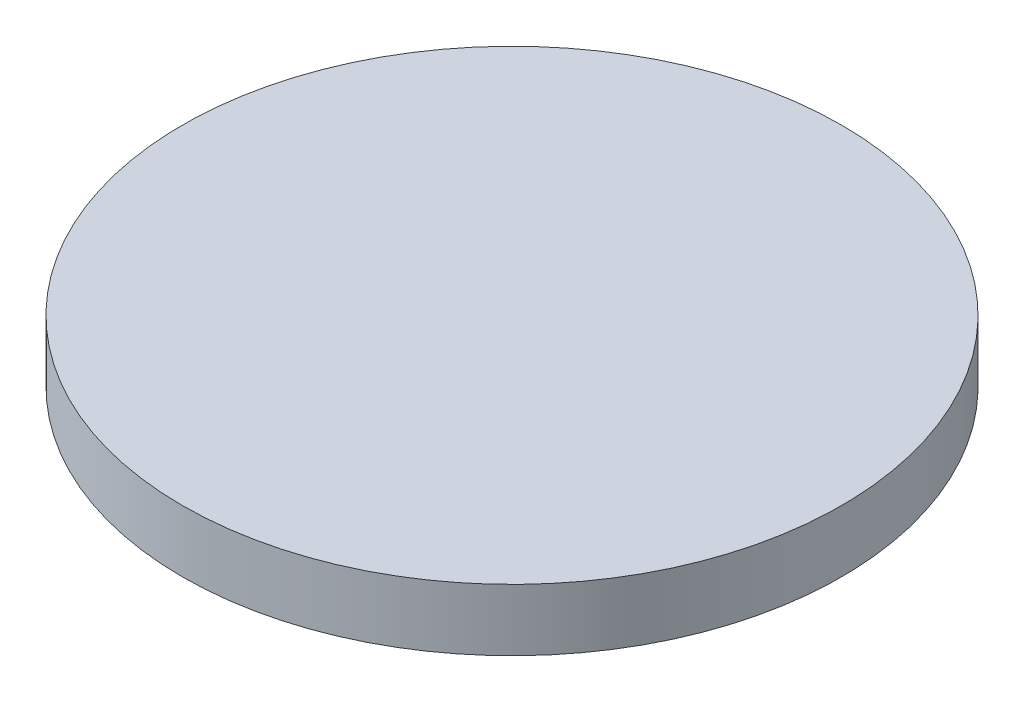
SolidWorks part; units mm, degrees
material "ABS PC"
ref_plane "Front Plane" through (0, 0, 0) normal (0, 0, 1) x (1, 0, 0)
ref_plane "Top Plane" through (0, 0, 0) normal (0, 1, 0) x (1, 0, 0)
ref_plane "Right Plane" through (0, 0, 0) normal (1, 0, 0) x (0, 0, -1)
sketch "Sketch1" plane through (0, 0, 0) normal (0, 1, 0) x (1, 0, 0)
  circle A1 centre (0, 0) radius 4.05
  circle A2 centre (0, 0) radius 16
  circle A3 centre (0, 8) radius 1.1
  circle A4 centre (5.6569, 5.6569) radius 1.1
  circle A5 centre (8, 0) radius 1.1
  circle A6 centre (5.6569, -5.6569) radius 1.1
  circle A7 centre (0, -8) radius 1.1
  circle A8 centre (-5.6569, -5.6569) radius 1.1
  circle A9 centre (-8, 0) radius 1.1
  circle A10 centre (-5.6569, 5.6569) radius 1.1
  dimension "D1" = 8
  dimension "D2" = 8
  dimension "D3" = 8.1
  dimension "D4" = 2.2
extrude "Boss-Extrude1" add sketch "Sketch1" along normal blind 3 contours A2 A10 A9 A8 A7 A6 A5 A4 A3 A1 | A1 | A9 | A10 | A3 | A6 | A7 | A8
